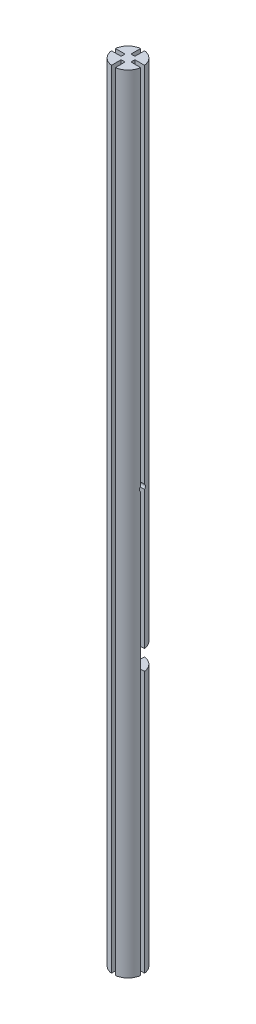
SolidWorks part; units mm, degrees
ref_plane "Front Plane" through (0, 0, 0) normal (0, 0, 1) x (1, 0, 0)
ref_plane "Top Plane" through (0, 0, 0) normal (0, 1, 0) x (1, 0, 0)
ref_plane "Right Plane" through (0, 0, 0) normal (1, 0, 0) x (0, 0, -1)
sketch "Sketch1" plane through (0, 0, 0) normal (0, 1, 0) x (1, 0, 0)
  line L5 (0, 194.8226) -> (0, 75) construction
  line L18 (-10, 74.3303) -> (-10, 25)
  line L19 (-10, 25) -> (10, 25)
  line L20 (10, 74.3303) -> (10, 25)
  line L21 (-29.2048, 0) -> (25.2155, 0) construction
  line L22 (74.3303, -10) -> (25, -10)
  line L23 (74.3303, 10) -> (25, 10)
  line L24 (25, 10) -> (25, -10)
  line L25 (-10, -74.3303) -> (-10, -25)
  line L26 (10, -74.3303) -> (10, -25)
  line L27 (10, -25) -> (-10, -25)
  line L28 (-74.3303, 10) -> (-25, 10)
  line L29 (-74.3303, -10) -> (-25, -10)
  line L30 (-25, -10) -> (-25, 10)
  line L31 (0, 75) -> (0, 25) construction
  line L32 (0, 25) -> (0, -243.8201) construction
  arc A2 (-10, 74.3303) -> (-74.3303, 10) centre (0, 0) ccw
  arc A3 (-74.3303, -10) -> (-10, -74.3303) centre (0, 0) ccw
  arc A4 (10, -74.3303) -> (74.3303, -10) centre (0, 0) ccw
  arc A5 (74.3303, 10) -> (10, 74.3303) centre (0, 0) ccw
  arc A6 (-10, 74.3303) -> (29.2889, 69.0446) centre (0, 0) cw
  point P1 (0, 25)
  point P4 (0, 93.7498)
  point P24 (-100, 0)
  point P29 (0, 0)
  point P30 (0, 0)
  dimension "D1" = 150
  dimension "D2" = 20
  dimension "D3" = 50
  dimension "D4" = 4
extrude "Boss-Extrude2" add sketch "Sketch1" along normal blind 4000 contours A2 L28 L30 L29 A3 L25 L27 L26 A4 L22 L24 L23 A5 L20 L19 L18
sketch "Sketch2" plane through (0, 0, 0) normal (0, 1, 0) x (1, 0, 0)
  line L0 (-76.3724, 74.3303) -> (-76.3724, 0)
  line L1 (74.3303, 74.3303) -> (74.3303, 0)
  line L2 (74.3303, 74.3303) -> (-76.3724, 74.3303)
  line L3 (74.3303, 0) -> (-76.3724, 0)
extrude "Cut-Extrude2" cut sketch "Sketch2" against normal mid plane 100 from offset 1380
ref_plane "Plane1" through (74.3303, 0, 0) normal (1, 0, 0) x (0, 0, -1)
ref_plane "Plane2" through (0, 0, -74.3303) normal (0, 0, -1) x (-1, 0, 0)
sketch "Sketch3" plane through (74.3303, 0, 0) normal (1, 0, 0) x (0, 0, -1)
  circle A0 centre (0, 2143) radius 15.2
extrude "Cut-Extrude3" cut sketch "Sketch3" against normal through all
